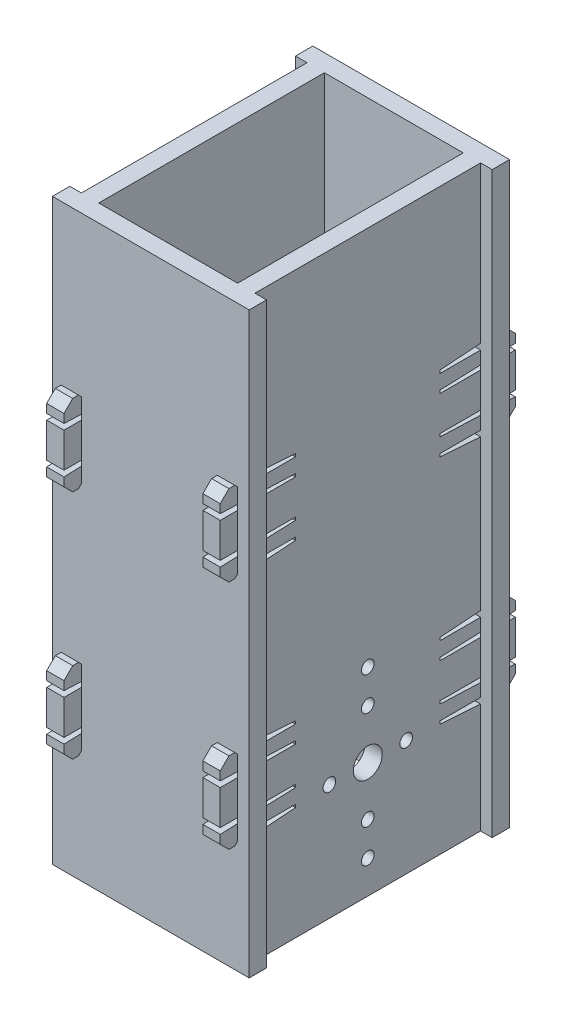
SolidWorks part; units mm, degrees
ref_plane "Front Plane" through (0, 0, 0) normal (0, 0, 1) x (1, 0, 0)
ref_plane "Top Plane" through (0, 0, 0) normal (0, 1, 0) x (1, 0, 0)
ref_plane "Right Plane" through (0, 0, 0) normal (1, 0, 0) x (0, 0, -1)
sketch "Sketch2" plane through (0, 0, 0) normal (0, 1, 0) x (1, 0, 0)
  line L0 (0, 0) -> (0, 45)
  line L1 (0, 45) -> (30, 45)
  line L2 (30, 45) -> (30, 0)
  line L3 (30, 0) -> (0, 0)
  line L5 (3, 42) -> (27, 42)
  line L7 (27, 3) -> (3, 3)
  line L8 (3, 45) -> (3, 0)
  line L9 (27, 45) -> (27, 0)
  line L10 (15, 3) -> (15, 42) construction
  line L11 (0, 22.5) -> (30, 22.5) construction
  dimension "D1" = 30
  dimension "D2" = 45
  dimension "D3" = 3
  dimension "D4" = 3
  dimension "D5" = 3
  dimension "D6" = 3
ref_plane "Plane2" through (3, 0, 0) normal (-1, 0, 0) x (0, 0, 1)
sketch "Sketch3" plane through (3, 0, 0) normal (-1, 0, 0) x (0, 0, 1)
  line L0 (-42, 0) -> (-3, 0)
  line L3 (-3, 100) -> (-42, 100)
  line L5 (-48, 23) -> (-48, 29)
  line L6 (-48, 26) -> (-34.2464, 26) construction
  line L7 (-46.7464, 26) -> (-37.442, 26) construction
  line L8 (-48, 63) -> (-48, 69)
  line L9 (-48, 66) -> (-34.4746, 66) construction
  line L10 (-46.9746, 66) -> (-37.6702, 66) construction
  line L11 (-22.5, 0) -> (-22.5, 66) construction
  line L12 (1.9746, 66) -> (-7.3298, 66) construction
  line L13 (1.7464, 26) -> (-7.558, 26) construction
  line L14 (3, 63) -> (3, 69)
  line L15 (3, 23) -> (3, 29)
  line L16 (-42, 100) -> (-42, 73)
  line L17 (-42, 59) -> (-42, 33)
  line L18 (-42, 19) -> (-42, 0)
  line L19 (-3, 0) -> (-3, 19)
  line L20 (-3, 33) -> (-3, 59)
  line L21 (-3, 73) -> (-3, 100)
  line L22 (-45, 0) -> (0, 0) construction
  line L23 (-45, 0) -> (0, 0) construction
  line L24 (-22.5, 20) -> (-29.1325, 20) construction
  circle A0 centre (-29.1325, 20) radius 1.0922
  circle A1 centre (-22.5, 5.7) radius 1.0922
  circle A2 centre (-22.5, 11.5) radius 1.0922
  circle A3 centre (-22.5, 28.5) radius 1.0922
  circle A4 centre (-22.5, 34.3) radius 1.0922
  circle A5 centre (-15.8675, 20) radius 1.0922
  circle A6 centre (-22.5, 20) radius 2.5
  line B0 (-35, 32.5) -> (-42, 33)
  line B1 (-35, 32) -> (-35, 32.5)
  line B2 (-44, 32) -> (-35, 32)
  line B3 (-45, 32.5) -> (-44, 32)
  line B4 (-45.5, 33) -> (-45, 32.5)
  line B5 (-46.5, 33) -> (-45.5, 33)
  line B6 (-48, 31.5) -> (-46.5, 33)
  line B7 (-48, 30) -> (-48, 31.5)
  line B8 (-35, 29) -> (-35, 29.5)
  line B9 (-35, 29.5) -> (-48, 30)
  line B10 (-48, 29) -> (-35, 29)
  line B11 (-48, 23) -> (-35, 23)
  line B12 (-35, 23) -> (-35, 22.5)
  line B13 (-35, 22.5) -> (-48, 22)
  line B14 (-48, 22) -> (-48, 20.5)
  line B15 (-48, 20.5) -> (-46.5, 19)
  line B16 (-46.5, 19) -> (-45.5, 19)
  line B17 (-45.5, 19) -> (-45, 19.5)
  line B18 (-45, 19.5) -> (-44, 20)
  line B19 (-44, 20) -> (-35, 20)
  line B20 (-35, 20) -> (-35, 19.5)
  line B21 (-35, 19.5) -> (-42, 19)
  line B22 (-48, 63) -> (-35, 63)
  line B23 (-35, 63) -> (-35, 62.5)
  line B24 (-35, 62.5) -> (-48, 62)
  line B25 (-48, 62) -> (-48, 60.5)
  line B26 (-48, 60.5) -> (-46.5, 59)
  line B27 (-46.5, 59) -> (-45.5, 59)
  line B28 (-45.5, 59) -> (-45, 59.5)
  line B29 (-45, 59.5) -> (-44, 60)
  line B30 (-44, 60) -> (-35, 60)
  line B31 (-35, 60) -> (-35, 59.5)
  line B32 (-35, 59.5) -> (-42, 59)
  line B33 (-35, 72.5) -> (-42, 73)
  line B34 (-35, 72) -> (-35, 72.5)
  line B35 (-44, 72) -> (-35, 72)
  line B36 (-45, 72.5) -> (-44, 72)
  line B37 (-45.5, 73) -> (-45, 72.5)
  line B38 (-46.5, 73) -> (-45.5, 73)
  line B39 (-48, 71.5) -> (-46.5, 73)
  line B40 (-48, 70) -> (-48, 71.5)
  line B41 (-35, 69) -> (-35, 69.5)
  line B42 (-35, 69.5) -> (-48, 70)
  line B43 (-48, 69) -> (-35, 69)
  line B44 (-10, 32.5) -> (-3, 33)
  line B45 (-10, 32) -> (-10, 32.5)
  line B46 (-1, 32) -> (-10, 32)
  line B47 (0, 32.5) -> (-1, 32)
  line B48 (0.5, 33) -> (0, 32.5)
  line B49 (1.5, 33) -> (0.5, 33)
  line B50 (3, 31.5) -> (1.5, 33)
  line B51 (3, 30) -> (3, 31.5)
  line B52 (-10, 29) -> (-10, 29.5)
  line B53 (-10, 29.5) -> (3, 30)
  line B54 (3, 29) -> (-10, 29)
  line B55 (3, 23) -> (-10, 23)
  line B56 (-10, 23) -> (-10, 22.5)
  line B57 (-10, 22.5) -> (3, 22)
  line B58 (3, 22) -> (3, 20.5)
  line B59 (3, 20.5) -> (1.5, 19)
  line B60 (1.5, 19) -> (0.5, 19)
  line B61 (0.5, 19) -> (0, 19.5)
  line B62 (0, 19.5) -> (-1, 20)
  line B63 (-1, 20) -> (-10, 20)
  line B64 (-10, 20) -> (-10, 19.5)
  line B65 (-10, 19.5) -> (-3, 19)
  line B66 (-10, 72.5) -> (-3, 73)
  line B67 (-10, 72) -> (-10, 72.5)
  line B68 (-1, 72) -> (-10, 72)
  line B69 (0, 72.5) -> (-1, 72)
  line B70 (0.5, 73) -> (0, 72.5)
  line B71 (1.5, 73) -> (0.5, 73)
  line B72 (3, 71.5) -> (1.5, 73)
  line B73 (3, 70) -> (3, 71.5)
  line B74 (-10, 69) -> (-10, 69.5)
  line B75 (-10, 69.5) -> (3, 70)
  line B76 (3, 69) -> (-10, 69)
  line B77 (3, 63) -> (-10, 63)
  line B78 (-10, 63) -> (-10, 62.5)
  line B79 (-10, 62.5) -> (3, 62)
  line B80 (3, 62) -> (3, 60.5)
  line B81 (3, 60.5) -> (1.5, 59)
  line B82 (1.5, 59) -> (0.5, 59)
  line B83 (0.5, 59) -> (0, 59.5)
  line B84 (0, 59.5) -> (-1, 60)
  line B85 (-1, 60) -> (-10, 60)
  line B86 (-10, 60) -> (-10, 59.5)
  line B87 (-10, 59.5) -> (-3, 59)
  dimension "D9" = 2.1844
  dimension "D10" = 5
  dimension "D1" = 39
  dimension "D2" = 100
  dimension "D3" = 6
  dimension "D4" = 20
  dimension "D5" = 12
  dimension "D6" = 6
  dimension "D7" = 60
  dimension "D8" = 20
  dimension "D11" = 14.3
  dimension "D12" = 6.6325
  dimension "D13" = 8.5
sketch_block_instance "Block-Snap-L-12"
sketch_block "Block-Snap-L" parameters "D1"=13, "D2"=0.5, "D3"=1, "D4"=1.5, "D5"=1.5, "D6"=0.5, "D7"=1, "D8"=7, "D9"=1, "D10"=0.5, "D11"=1, "D12"=1.5, "D13"=2.5
sketch_block_instance "Block-Snap-R-23"
sketch_block "Block-Snap-R" parameters "D1"=13, "D2"=0.5, "D3"=1, "D4"=0.5, "D5"=1, "D6"=2.5, "D7"=1.5, "D8"=1.5, "D9"=1.5, "D10"=1, "D11"=0.5, "D12"=1, "D13"=7
sketch_block_instance "Block-Snap-R-24"
sketch_block_instance "Block-Snap-L-13"
sketch_block_instance "Block-Snap-L-14"
sketch_block_instance "Block-Snap-R-25"
sketch_block_instance "Block-Snap-L-15"
sketch_block_instance "Block-Snap-R-26"
extrude "Boss-Extrude2" add sketch "Sketch3" along normal blind 3 contours B87 B86 B85 B84 B83 B82 B81 B80 B79 B78 B77 L14 B76 B74 B75 B73 B72 B71 B70 B69 B68 B67 B66 L21 L3 L16 B33 B34 B35 B36 B37 B38 B39 B40 B42 B41 B43 L8 B22 B23 B24 B25 B26 B27 B28 B29 B30 B31 B32 L17 B0
ref_plane "Plane3" through (15, 0, 0) normal (1, 0, 0) x (0, 0, -1)
ref_plane "Plane4" through (0, 0, -3) normal (0, 0, 1) x (1, 0, 0)
sketch "Sketch6" plane through (0, 0, -3) normal (0, 0, 1) x (1, 0, 0)
  line L1 (30, 72) -> (30, 60)
  line L2 (27, 72) -> (30, 72)
  line L4 (30, 100) -> (0, 100)
  line L5 (0, 33) -> (0, 59) construction
  line L7 (3, 32) -> (3, 20)
  line L8 (3, 20) -> (0, 20)
  line L9 (0, 20) -> (0, 32)
  line L10 (0, 32) -> (3, 32)
  line L11 (-2, 0) -> (32, 0)
  line L13 (32, 100) -> (-2, 100)
  line L14 (-2, 100) -> (-2, 0)
  line L15 (15, 0) -> (15, 9.0151) construction
  line L16 (0, 60) -> (3, 60)
  line L17 (3, 33) -> (3, 59) construction
  line L18 (3, 60) -> (3, 72)
  line L19 (3, 73) -> (3, 100) construction
  line L20 (3, 72) -> (0, 72)
  line L21 (0, 73) -> (0, 100) construction
  line L22 (0, 72) -> (0, 60)
  line L23 (27, 60) -> (27, 72)
  line L24 (30, 60) -> (27, 60)
  line L25 (32, 100) -> (32, 0)
  line L26 (30, 32) -> (27, 32)
  line L27 (30, 20) -> (30, 32)
  line L28 (27, 20) -> (30, 20)
  line L29 (27, 32) -> (27, 20)
  point P38 (15, 100)
  dimension "D1" = 2
  dimension "D2" = 2
  dimension "D3" = 12
  dimension "D4" = 3
  dimension "D5" = 100
  dimension "D6" = 20
  dimension "D7" = 12
  dimension "D8" = 60
extrude "Boss-Extrude3" add sketch "Sketch6" along normal blind 3
ref_plane "Plane5" through (0, 0, -22.5) normal (0, 0, -1) x (-1, 0, 0)
mirror "Mirror3" about plane through (0, 0, -22.5) normal (0, 0, -1) of "Boss-Extrude3"
mirror "Mirror4" about plane through (15, 0, 0) normal (1, 0, 0) of "Boss-Extrude2"
